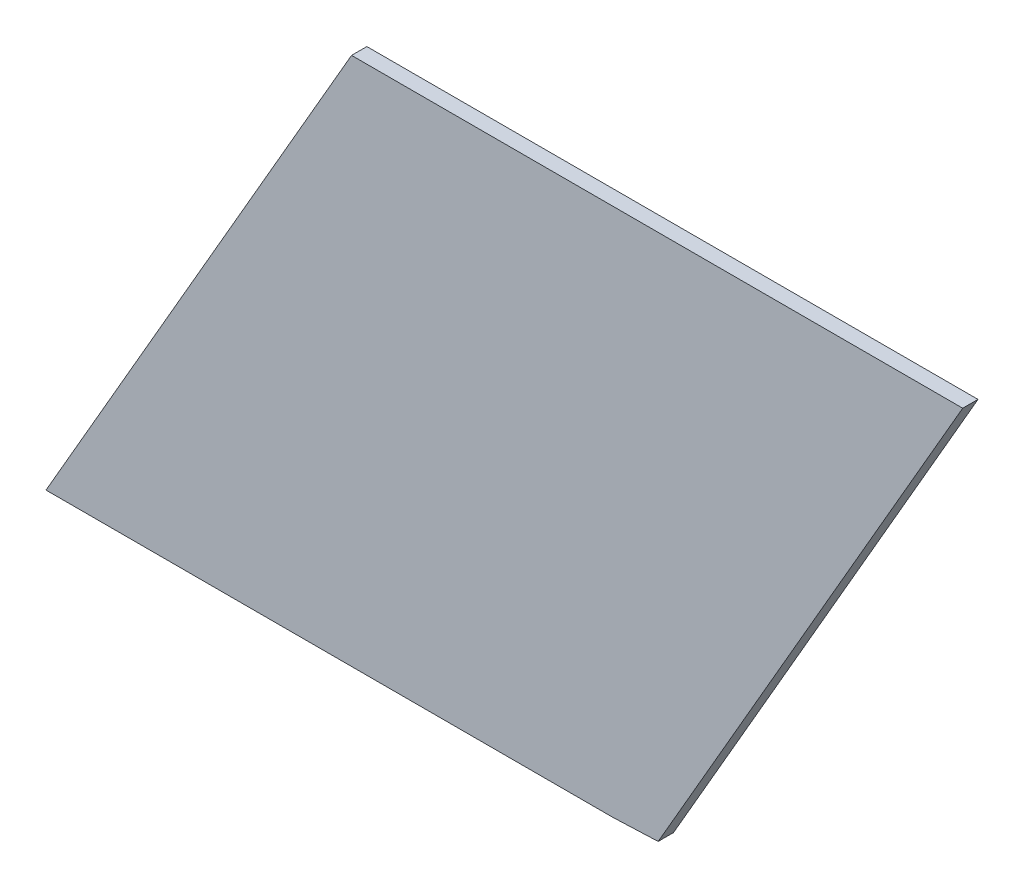
SolidWorks part; units mm, degrees
ref_plane "Front Plane" through (0, 0, 0) normal (0, 0, 1) x (1, 0, 0)
ref_plane "Top Plane" through (0, 0, 0) normal (0, 1, 0) x (1, 0, 0)
ref_plane "Right Plane" through (0, 0, 0) normal (1, 0, 0) x (0, 0, -1)
sketch "Sketch1" plane through (0, 0, 0) normal (0, 0, 1) x (1, 0, 0)
  line L1 (-328.2378, 112.9841) -> (-402.4643, 112.9841)
  line L2 (-402.4643, 112.9841) -> (-362.4643, 182.2661)
  line L3 (-362.4643, 182.2661) -> (-282.4643, 182.2661)
  line L4 (-282.4643, 182.2661) -> (-322.3289, 113.2185)
  line L5 (-322.3289, 113.2185) -> (-328.2378, 112.9841)
extrude "Boss-Extrude1" add sketch "Sketch1" along normal blind 2 contours L2 L3 L4 L5 L1
